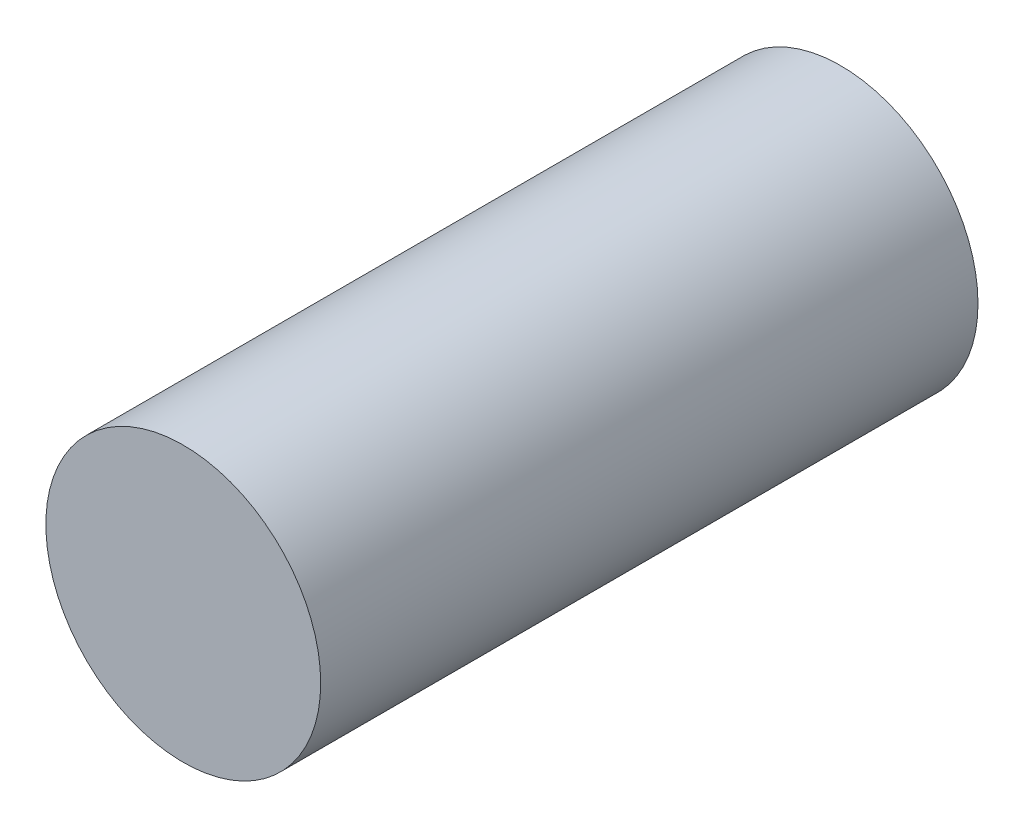
SolidWorks part; units mm, degrees
ref_plane "Front Plane" through (0, 0, 0) normal (0, 0, 1) x (1, 0, 0)
ref_plane "Top Plane" through (0, 0, 0) normal (0, 1, 0) x (1, 0, 0)
ref_plane "Right Plane" through (0, 0, 0) normal (1, 0, 0) x (0, 0, -1)
sketch "Sketch1" plane through (0, 0, 0) normal (0, 0, 1) x (1, 0, 0)
  circle A0 centre (-0.2606, 10.6178) radius 10.621
  dimension "D1" = 21.242
extrude "Extrude1" add sketch "Sketch1" along normal mid plane 50.8
